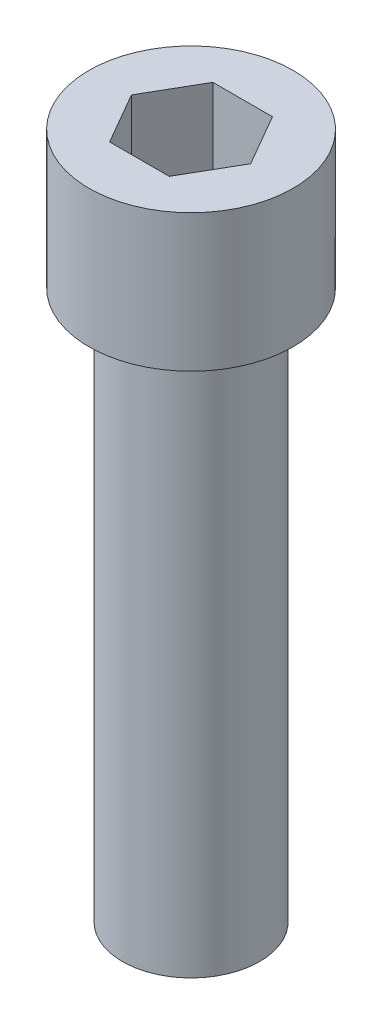
SolidWorks part; units mm, degrees
ref_plane "Front"
ref_plane "Top" through (0, 0, 0) normal (0, 1, 0) x (1, 0, 0)
ref_plane "Right" through (0, 0, 0) normal (1, 0, 0) x (0, 0, -1)
sketch "Sketch1" plane through (0, 0, 0) normal (0, 0, 1) x (1, 0, 0)
  line L0 (0, 0) -> (3.175, 0)
  line L1 (3.175, 0) -> (3.175, 25.4)
  line L2 (3.175, 25.4) -> (4.7244, 25.4)
  line L3 (0, 31.75) -> (4.7244, 31.75)
  line L4 (4.7244, 31.75) -> (4.7244, 25.4)
  line L5 (0, 0) -> (0, 31.75)
  line L6 (0, 0) -> (0, 30.7805) construction
  dimension "MajorDia" = 6.35
  dimension "Length" = 25.4
  dimension "HeadHeight" = 6.35
  dimension "HeadDiam" = 9.4488
revolve "Screw revolve" add sketch "Sketch1" angle 360 about L6
sketch "Sketch2" plane through (0, 31.75, 0) normal (0, 1, 0) x (-1, 0, 0)
  line L1 (-2.757, 0) -> (-1.3785, -2.3876)
  line L2 (-1.3785, -2.3876) -> (1.3785, -2.3876)
  line L3 (1.3785, -2.3876) -> (2.757, 0)
  line L4 (2.757, 0) -> (1.3785, 2.3876)
  line L5 (1.3785, 2.3876) -> (-1.3785, 2.3876)
  line L6 (-1.3785, 2.3876) -> (-2.757, 0)
  circle A0 centre (0, 0) radius 2.3876 construction
  dimension "HexWidth" = 4.7752
extrude "Hex Cut" cut sketch "Sketch2" against normal blind 3.81
